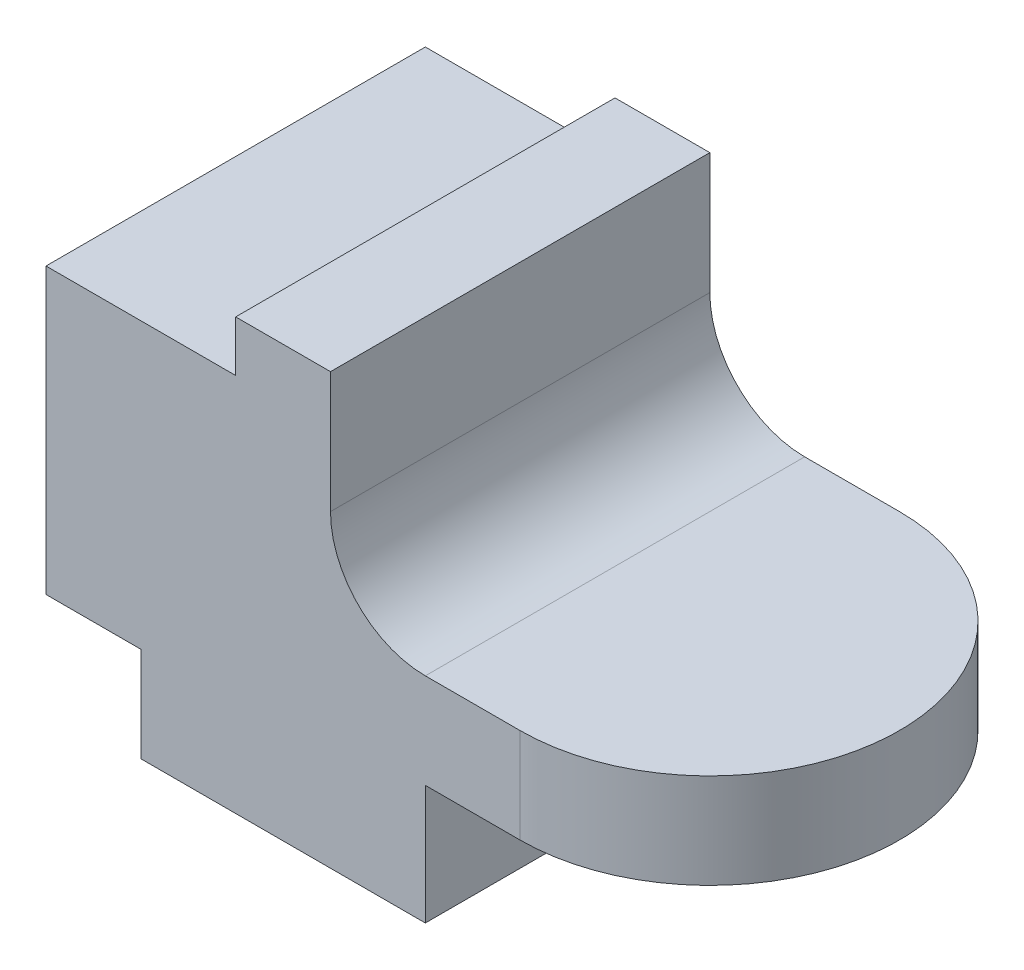
SolidWorks part; units mm, degrees
ref_plane "Front Plane" through (0, 0, 0) normal (0, 0, 1) x (1, 0, 0)
ref_plane "Top Plane" through (0, 0, 0) normal (0, 1, 0) x (1, 0, 0)
ref_plane "Right Plane" through (0, 0, 0) normal (1, 0, 0) x (0, 0, -1)
sketch "Sketch1" plane through (0, 0, 0) normal (0, 0, 1) x (1, 0, 0)
  line L0 (-15.8091, 23.9004) -> (-5.8091, 23.9004)
  line L1 (-5.8091, 23.9004) -> (-5.8091, 11.1203)
  line L2 (4.1909, 1.1203) -> (34.1909, 1.1203)
  line L3 (34.1909, 1.1203) -> (34.1909, -8.8797)
  line L4 (34.1909, -8.8797) -> (4.1909, -8.8797)
  line L5 (4.1909, -8.8797) -> (4.1909, -21.4523)
  line L6 (4.1909, -21.4523) -> (-25.8091, -21.4523)
  line L7 (-25.8091, -21.4523) -> (-25.8091, -11.4523)
  line L8 (-25.8091, -11.4523) -> (-35.8091, -11.4523)
  line L9 (-35.8091, -11.4523) -> (-35.8091, 18.5477)
  line L10 (-35.8091, 18.5477) -> (-15.8091, 18.5477)
  line L11 (-15.8091, 18.5477) -> (-15.8091, 23.9004)
  arc A0 (4.1909, 1.1203) -> (-5.8091, 11.1203) centre (4.1909, 11.1203) cw
  dimension "D9" = 10
  dimension "D1" = 30
  dimension "D2" = 10
  dimension "D3" = 10
  dimension "D4" = 30
  dimension "D5" = 30
  dimension "D6" = 10
  dimension "D7" = 20
  dimension "D8" = 40
extrude "Boss-Extrude1" add sketch "Sketch1" along normal blind 40
sketch "Sketch3" plane through (0, 1.1203, 0) normal (0, 1, 0) x (1, 0, 0)
  line L0 (34.1909, -40) -> (34.1909, 0) construction
  line L1 (19.1909, 0) -> (19.1909, -40) construction
  line L2 (34.1909, 0) -> (4.1909, 0) construction
  line L3 (34.1909, -40) -> (4.1909, -40) construction
  line L4 (19.1909, -20) -> (8.1924, -20) construction
  line L5 (14.1909, 0) -> (-35.8091, 0)
  line L6 (-35.8091, 0) -> (-35.8091, -40)
  line L7 (-35.8091, -40) -> (14.1909, -40)
  arc A0 (14.1909, -40) -> (14.1909, 0) centre (14.1909, -20) ccw
  dimension "D1" = 40
extrude "Cut-Extrude1" cut sketch "Sketch3" against normal blind 40 flip side to cut contours A0 L5 L6 L7
